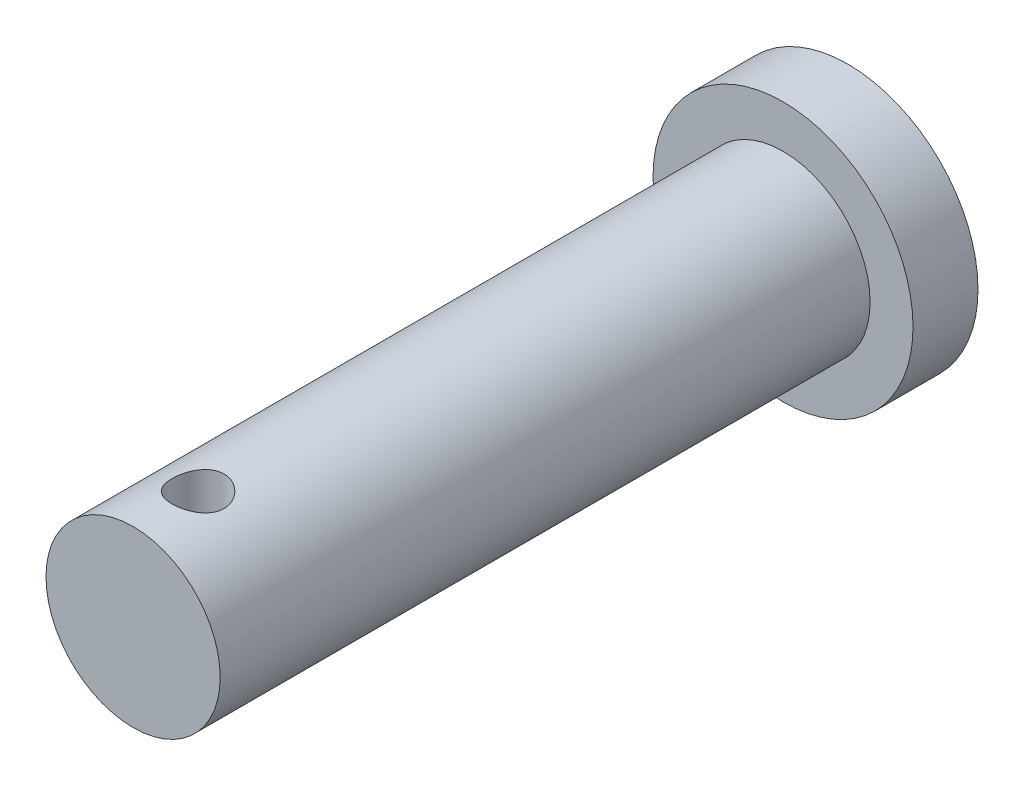
SolidWorks part; units mm, degrees
ref_plane "Front Plane" through (0, 0, 0) normal (0, 0, 1) x (1, 0, 0)
ref_plane "Top Plane" through (0, 0, 0) normal (0, 1, 0) x (1, 0, 0)
ref_plane "Right Plane" through (0, 0, 0) normal (1, 0, 0) x (0, 0, -1)
sketch "Sketch2" plane through (0, 0, 0) normal (0, 0, 1) x (1, 0, 0)
  circle A0 centre (0, 0) radius 6.7
  dimension "D1" = 13.4
extrude "Boss-Extrude1" add sketch "Sketch2" along normal blind 55 contours A0
sketch "Sketch3" plane through (0, 0, 0) normal (0, 0, -1) x (-1, 0, 0)
  circle A0 centre (0, 0) radius 10
  dimension "D1" = 20
extrude "Boss-Extrude2" add sketch "Sketch3" against normal blind 5
sketch "Sketch5" plane through (0, 0, 0) normal (0, 1, 0) x (1, 0, 0)
  line L0 (-6.7, -55) -> (6.7, -55) construction
  circle A0 centre (0, -50) radius 2
  dimension "D1" = 5
  dimension "D2" = 4
extrude "Cut-Extrude1" cut sketch "Sketch5" against normal blind 15 and the other way blind 10
